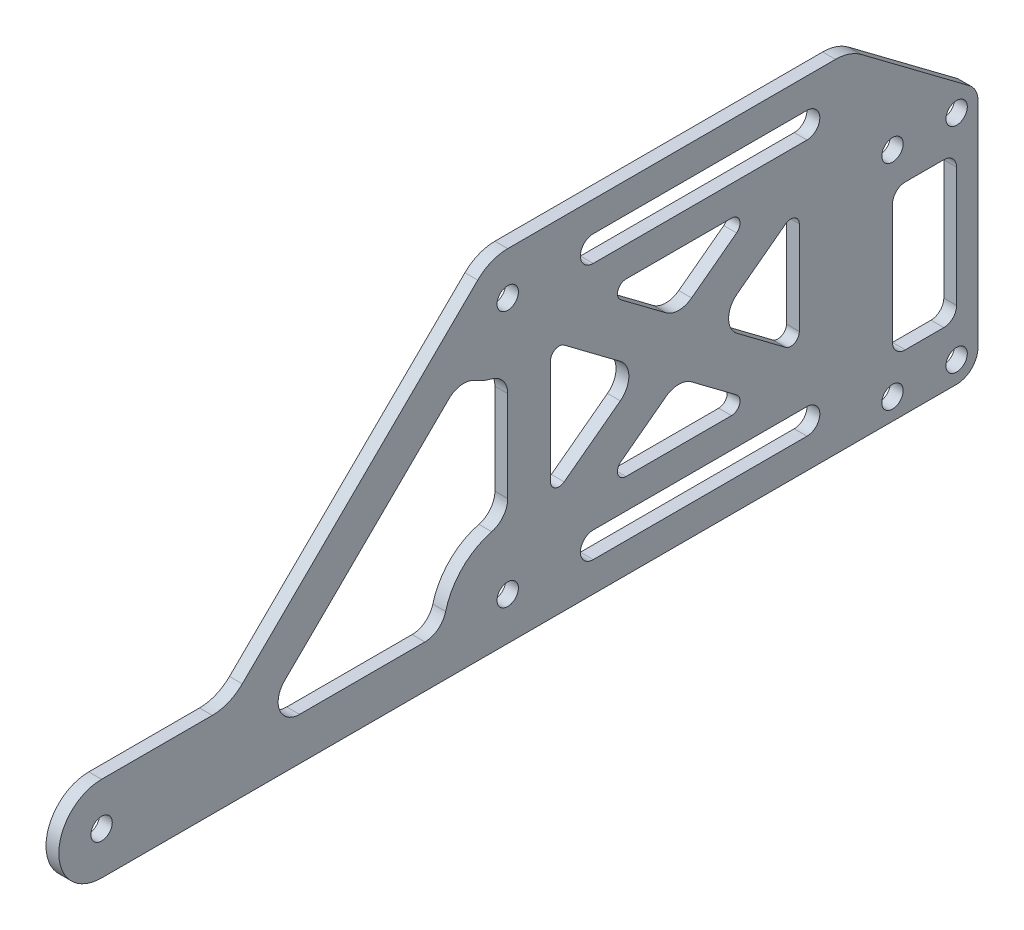
SolidWorks part; units mm, degrees
material "AISI 304"
ref_plane "前视基准面" through (0, 0, 0) normal (0, 0, 1) x (1, 0, 0)
ref_plane "上视基准面" through (0, 0, 0) normal (0, 1, 0) x (1, 0, 0)
ref_plane "右视基准面" through (0, 0, 0) normal (1, 0, 0) x (0, 0, -1)
sketch "草图1" plane through (0, 0, 0) normal (1, 0, 0) x (0, 0, -1)
  line L0 (0, -10) -> (175, -10)
  line L1 (0, 0) -> (95, 0) construction
  line L2 (95, 0) -> (95, 60) construction
  line L3 (0, 10) -> (25.9015, 10)
  line L4 (32.9196, 12.8764) -> (87.9819, 67.1236)
  line L5 (95, 70) -> (171.6667, 70)
  line L6 (185, 81.8897) -> (185, -26.3023) construction
  line L7 (175, 81.8897) -> (175, -26.3023) construction
  line L8 (200, 81.8897) -> (200, -26.3023) construction
  line L9 (207.6575, 20) -> (180.105, 20) construction
  line L10 (207.6575, 45) -> (180.105, 45) construction
  line L11 (207.6575, -5) -> (180.105, -5) construction
  line L15 (95, 60) -> (34.0985, 0) construction
  line L16 (177.6667, 68) -> (203, 49)
  line L17 (46.298, 0) -> (75.6351, 0)
  line L22 (42.789, 8.5618) -> (81.2052, 46.4094)
  line L23 (95, 40.6351) -> (95, 19.3649)
  line L24 (95, 60) -> (175, 60) construction
  line L25 (95, 0) -> (175, 0) construction
  line L26 (95, 60) -> (175, 0) construction
  line L27 (95, 0) -> (175, 60) construction
  line L28 (108.2, 43.85) -> (121.3333, 34)
  line L29 (122.6667, 50) -> (147.3333, 50)
  line L30 (105, 42.25) -> (105, 17.75)
  line L32 (163.2017, 40.9013) -> (163.2017, 19.0987)
  line L33 (138, 38.5) -> (148.5333, 46.4)
  line L34 (121.4667, 46.4) -> (132, 38.5)
  line L35 (148.6667, 34) -> (160.0017, 42.5013)
  line L36 (108.2, 16.15) -> (121.3333, 26)
  line L37 (98, 64) -> (178, 4) construction
  line L38 (92, 56) -> (172, -4) construction
  line L39 (121.4667, 13.6) -> (132, 21.5)
  line L40 (148.6667, 26) -> (160.0017, 17.4987)
  line L41 (138, 21.5) -> (148.5333, 13.6)
  line L42 (122.6667, 10) -> (147.3333, 10)
  line L43 (175, -10) -> (200, -10)
  line L44 (205, 45) -> (205, -5)
  line L45 (115, 60) -> (165, 60) construction
  line L46 (115, 63) -> (165, 63)
  line L47 (115, 57) -> (165, 57)
  line L48 (115, 0) -> (165, 0) construction
  line L49 (115, 3) -> (165, 3)
  line L50 (115, -3) -> (165, -3)
  line L52 (188, 37) -> (197, 37)
  line L53 (185, 34) -> (185, 6)
  line L54 (188, 3) -> (197, 3)
  line L55 (200, 34) -> (200, 6)
  circle A0 centre (0, 0) radius 2.5
  arc A1 (0, 10) -> (0, -10) centre (0, 0) ccw
  circle A2 centre (95, 0) radius 2.5
  arc A4 (95, 70) -> (87.9819, 67.1236) centre (95, 60) ccw
  circle A5 centre (95, 60) radius 2.5
  arc A10 (32.9196, 12.8764) -> (25.9015, 10) centre (25.9015, 20) cw
  arc A18 (87.2857, 47.1357) -> (91.25, 45.4763) centre (95, 60) ccw
  arc A19 (91.25, 14.5237) -> (80.4763, 3.75) centre (95, 0) ccw
  arc A20 (75.6351, 0) -> (80.4763, 3.75) centre (75.6351, 5) ccw
  arc A21 (91.25, 14.5237) -> (95, 19.3649) centre (90, 19.3649) ccw
  arc A22 (95, 40.6351) -> (91.25, 45.4763) centre (90, 40.6351) ccw
  arc A23 (87.2857, 47.1357) -> (81.2052, 46.4094) centre (84.7143, 42.8476) ccw
  arc A24 (46.298, 0) -> (42.789, 8.5618) centre (46.298, 5) cw
  arc A27 (138, 21.5) -> (132, 21.5) centre (135, 17.5) ccw
  arc A28 (148.6667, 26) -> (148.6667, 34) centre (151.6667, 30) cw
  arc A29 (138, 38.5) -> (132, 38.5) centre (135, 42.5) cw
  arc A30 (121.3333, 26) -> (121.3333, 34) centre (118.3333, 30) ccw
  arc A31 (148.5333, 46.4) -> (147.3333, 50) centre (147.3333, 48) ccw
  arc A32 (121.4667, 46.4) -> (122.6667, 50) centre (122.6667, 48) cw
  arc A33 (163.2017, 19.0987) -> (160.0017, 17.4987) centre (161.2017, 19.0987) cw
  arc A34 (163.2017, 40.9013) -> (160.0017, 42.5013) centre (161.2017, 40.9013) ccw
  arc A35 (147.3333, 10) -> (148.5333, 13.6) centre (147.3333, 12) ccw
  arc A36 (122.6667, 10) -> (121.4667, 13.6) centre (122.6667, 12) cw
  arc A37 (108.2, 16.15) -> (105, 17.75) centre (107, 17.75) cw
  arc A38 (108.2, 43.85) -> (105, 42.25) centre (107, 42.25) ccw
  circle A41 centre (200, 45) radius 2.5
  circle A43 centre (200, -5) radius 2.5
  arc A44 (205, 45) -> (203, 49) centre (200, 45) ccw
  arc A45 (200, -10) -> (205, -5) centre (200, -5) ccw
  circle A46 centre (185, 45) radius 2.5
  circle A47 centre (185, -5) radius 2.5
  arc A48 (177.6667, 68) -> (171.6667, 70) centre (171.6667, 60) ccw
  arc A49 (115, 63) -> (115, 57) centre (115, 60) ccw
  arc A50 (165, 57) -> (165, 63) centre (165, 60) ccw
  arc A51 (115, 3) -> (115, -3) centre (115, 0) ccw
  arc A52 (165, -3) -> (165, 3) centre (165, 0) ccw
  arc A53 (185, 6) -> (188, 3) centre (188, 6) ccw
  arc A54 (197, 3) -> (200, 6) centre (197, 6) ccw
  arc A55 (200, 34) -> (197, 37) centre (197, 34) ccw
  arc A56 (188, 37) -> (185, 34) centre (188, 34) ccw
  point P39 (30, 10)
  point P40 (210, 81.8897)
  point P41 (210, -26.3023)
  point P50 (80, 0)
  point P53 (95, 15)
  point P59 (95, 45)
  point P62 (84.3146, 49.4728)
  point P66 (175, 70)
  point P68 (140, 60)
  point P73 (153.3333, 50)
  point P77 (98, -4)
  point P78 (178, 56)
  point P81 (92, 4)
  point P82 (172, 64)
  point P97 (135, 23.75)
  point P100 (143.3333, 30)
  point P105 (126.6667, 30)
  point P113 (153.3333, 10)
  point P116 (116.6667, 10)
  point P127 (140, 0)
  point P140 (200, 3)
  point P145 (185, 37)
  dimension "D1" = 5
  dimension "D2" = 20
  dimension "D5" = 5
  dimension "D7" = 5
  dimension "D8" = 20
  dimension "D15" = 5
  dimension "D16" = 5
  dimension "D17" = 5
  dimension "D18" = 5
  dimension "D19" = 10
  dimension "D22" = 5
  dimension "D25" = 30
  dimension "D26" = 30
  dimension "D23" = 5
  dimension "D24" = 5
  dimension "D27" = 5
  dimension "D28" = 5
  dimension "D29" = 35
  dimension "D30" = 10
  dimension "D31" = 36.87
  dimension "D32" = 36.87
  dimension "D41" = 5
  dimension "D42" = 5
  dimension "D43" = 5
  dimension "D44" = 5
  dimension "D46" = 2
  dimension "D47" = 2
  dimension "D48" = 2
  dimension "D49" = 2
  dimension "D50" = 2
  dimension "D51" = 2
  dimension "D52" = 2
  dimension "D53" = 2
  dimension "D55" = 45
  dimension "D20" = 10
  dimension "D21" = 10
  dimension "D54" = 3
  dimension "D57" = 3
  dimension "D62" = 3
  dimension "D3" = 95
  dimension "D6" = 60
  dimension "D9" = 30
  dimension "D10" = 80
  dimension "D33" = 10
  dimension "D34" = 10
  dimension "D35" = 11.7983
  dimension "D36" = 21.6667
  dimension "D39" = 21.6667
  dimension "D40" = 21.6667
  dimension "D45" = 106.26
  dimension "D56" = 50
  dimension "D58" = 45
  dimension "D59" = 50
  dimension "D60" = 8
  dimension "D61" = 8
  dimension "D11" = 10
  dimension "D12" = 15
  dimension "D13" = 25
  dimension "D14" = 25
  dimension "D37" = 5
  dimension "D38" = 5
extrude "凸台-拉伸1" add sketch "草图1" along normal blind 3
